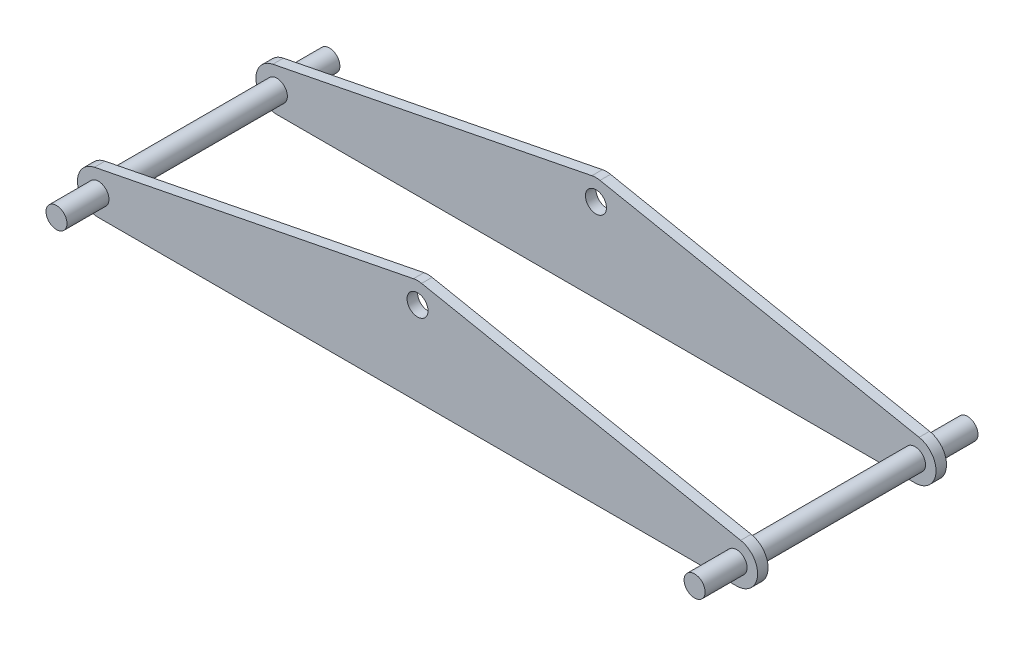
SolidWorks part; units mm, degrees
material "Cast Alloy Steel"
ref_plane "Front Plane" through (0, 0, 0) normal (0, 0, 1) x (1, 0, 0)
ref_plane "Top Plane" through (0, 0, 0) normal (0, 1, 0) x (1, 0, 0)
ref_plane "Right Plane" through (0, 0, 0) normal (1, 0, 0) x (0, 0, -1)
sketch "Sketch1" plane through (0, 0, 0) normal (0, 0, 1) x (1, 0, 0)
  line L0 (977.4957, 62.2982) -> (12.2957, 252.7982)
  line L1 (-965.2, -63.5) -> (965.2, -63.5)
  line L2 (-977.4957, 62.2982) -> (-12.2957, 252.7982)
  line L3 (0, 0) -> (0, 50000) construction
  arc A1 (12.2957, 252.7982) -> (-12.2957, 252.7982) centre (0, 190.5) ccw
  circle A2 centre (0, 190.5) radius 31.75
  circle A3 centre (-965.2, 0) radius 31.75
  arc A5 (-977.4957, 62.2982) -> (-965.2, -63.5) centre (-965.2, 0) ccw
  circle A7 centre (965.2, 0) radius 31.75
  arc A8 (977.4957, 62.2982) -> (965.2, -63.5) centre (965.2, 0) cw
  dimension "D1" = 1930.4
  dimension "D2" = 63.5
  dimension "D3" = 63.5
  dimension "D5" = 63.5
  dimension "D7" = 63.5
extrude "Boss-Extrude1" add sketch "Sketch1" along normal mid plane 31.75
sketch "Sketch4" plane through (0, 0, -15.875) normal (0, 0, -1) x (-1, 0, 0)
  circle A0 centre (-965.2, 0) radius 31.75
  circle A1 centre (965.2, 0) radius 31.75
extrude "Boss-Extrude3" add sketch "Sketch4" against normal blind 158.75 and the other way blind 666.75 contours A1 | A0
ref_plane "Plane2" through (0, 0, -523.875) normal (0, 0, -1) x (-1, 0, 0)
sketch "Sketch5" plane through (0, 0, -523.875) normal (0, 0, -1) x (-1, 0, 0)
  line L3 (977.4957, 62.2982) -> (12.2957, 252.7982)
  line L4 (-12.2957, 252.7982) -> (-977.4957, 62.2982)
  line L5 (-965.2, -63.5) -> (965.2, -63.5)
  line L6 (977.4957, 62.2982) -> (12.2957, 252.7982)
  line L7 (-12.2957, 252.7982) -> (-977.4957, 62.2982)
  line L8 (-965.2, -63.5) -> (965.2, -63.5)
  circle A1 centre (0, 190.5) radius 31.75
  circle A2 centre (0, 190.5) radius 31.75
  arc A3 (965.2, -63.5) -> (977.4957, 62.2982) centre (965.2, 0) ccw
  arc A4 (12.2957, 252.7982) -> (-12.2957, 252.7982) centre (0, 190.5) ccw
  arc A5 (-977.4957, 62.2982) -> (-965.2, -63.5) centre (-965.2, 0) ccw
  arc A6 (965.2, -63.5) -> (977.4957, 62.2982) centre (965.2, 0) ccw
  arc A7 (12.2957, 252.7982) -> (-12.2957, 252.7982) centre (0, 190.5) ccw
  arc A8 (-977.4957, 62.2982) -> (-965.2, -63.5) centre (-965.2, 0) ccw
  circle A9 centre (965.2, 0) radius 31.75
  circle A10 centre (965.2, 0) radius 31.75
  circle A11 centre (-965.2, 0) radius 31.75
  circle A12 centre (-965.2, 0) radius 31.75
  dimension "D1" = 0
  dimension "D2" = 0
  dimension "D3" = 0
  dimension "D4" = 0
extrude "Boss-Extrude4" add sketch "Sketch5" along normal blind 31.75 separate body contours L6 A7 L7 A8 L8 A6
